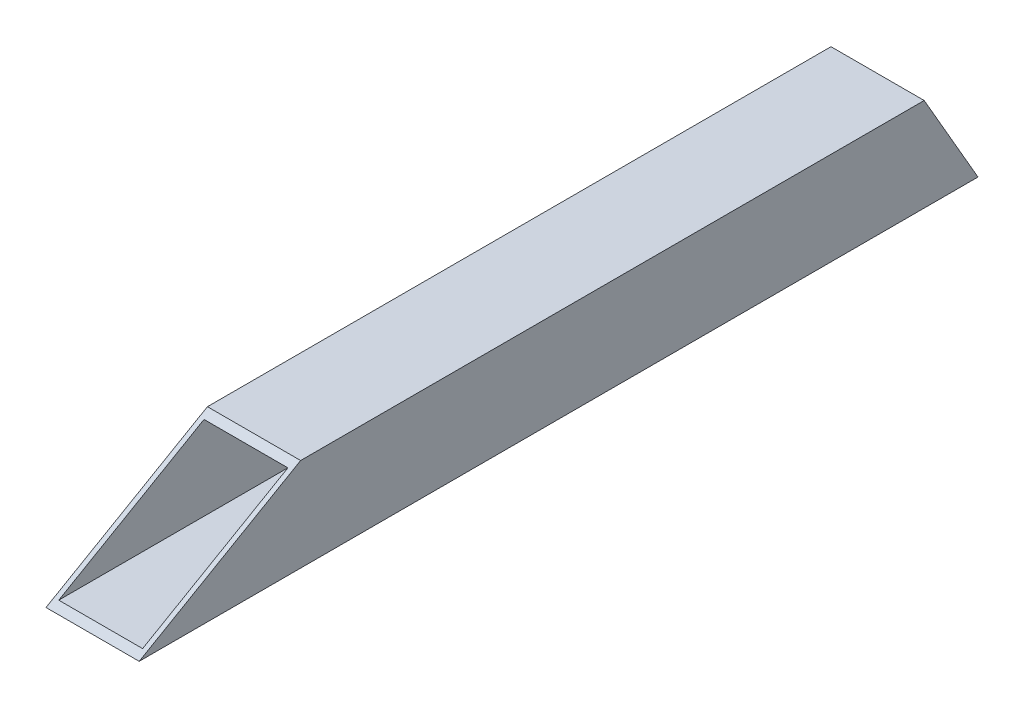
SolidWorks part; units mm, degrees
ref_plane "前视基准面" through (0, 0, 0) normal (0, 0, 1) x (1, 0, 0)
ref_plane "上视基准面" through (0, 0, 0) normal (0, 1, 0) x (1, 0, 0)
ref_plane "右视基准面" through (0, 0, 0) normal (1, 0, 0) x (0, 0, -1)
other "Configuration Table"
sketch "草图1" plane through (0, 0, 0) normal (0, 0, 1) x (1, 0, 0)
  line L1 (0, 0) -> (20, 0)
  line L2 (0, 0) -> (0, 20)
  line L3 (0, 20) -> (20, 20)
  line L4 (20, 0) -> (20, 20)
  line L5 (1, 1) -> (19, 1)
  line L6 (1, 1) -> (1, 19)
  line L7 (1, 19) -> (19, 19)
  line L8 (19, 1) -> (19, 19)
  dimension "D1" = 20
  dimension "D2" = 20
  dimension "D3" = 1
  dimension "D4" = 1
  dimension "D5" = 1
  dimension "D6" = 1
extrude "凸台-拉伸1" add sketch "草图1" along normal blind 180
sketch "草图2" plane through (20, 0, 0) normal (1, 0, 0) x (0, 0, -1)
  line L0 (-180, 20) -> (-180, 0)
  line L1 (-180, 0) -> (-145.359, 20)
  line L2 (-180, 20) -> (0, 20) construction
  line L3 (-145.359, 20) -> (-180, 20)
  line L4 (-11.547, 20) -> (0, 20)
  line L5 (0, 20) -> (0, 0)
  line L6 (0, 0) -> (-11.547, 20)
  dimension "D1" = 60
extrude "切除-拉伸1" cut sketch "草图2" against normal blind 250
